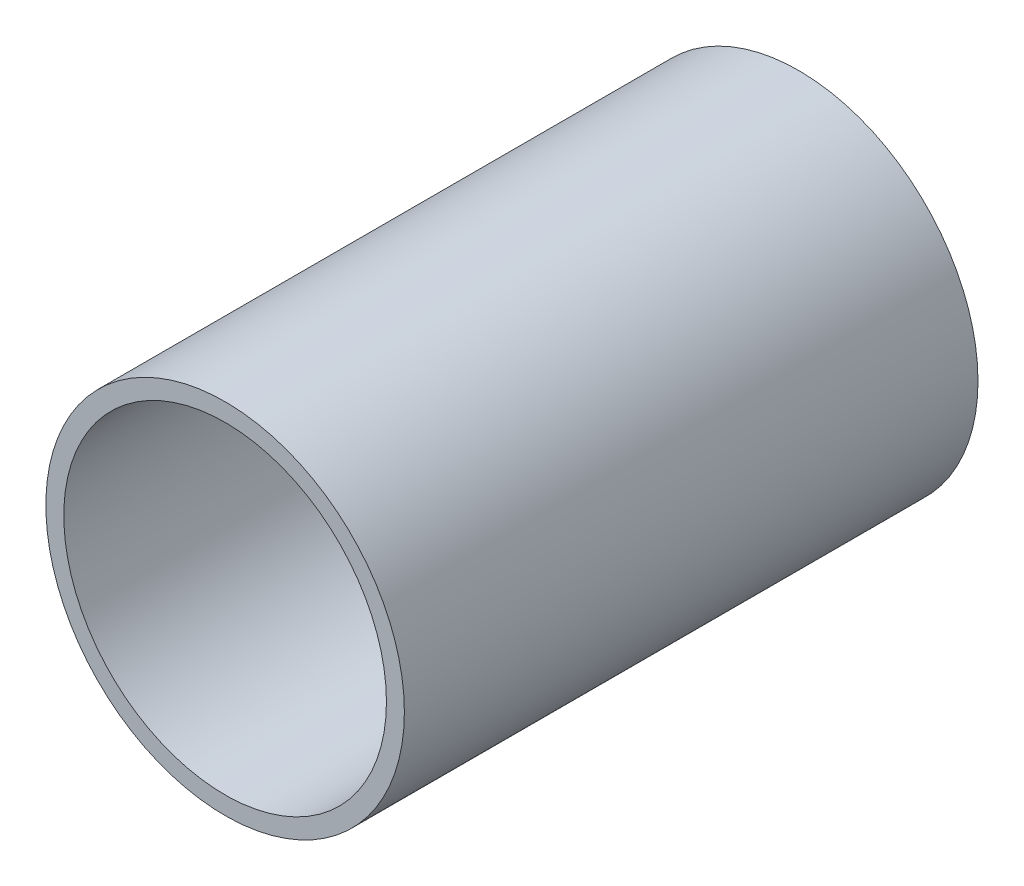
SolidWorks part; units mm, degrees
material "PVC Rigid"
ref_plane "Front" through (0, 0, 0) normal (0, 0, 1) x (1, 0, 0)
ref_plane "Top" through (0, 0, 0) normal (0, 1, 0) x (1, 0, 0)
ref_plane "Right" through (0, 0, 0) normal (1, 0, 0) x (0, 0, -1)
sketch "Sketch1" plane through (0, 0, 0) normal (0, 0, 1) x (1, 0, 0)
  circle A0 centre (0, 0) radius 45
  circle A1 centre (0, 0) radius 50
  dimension "D1" = 90
  dimension "D2" = 100
extrude "Boss-Extrude1" add sketch "Sketch1" along normal mid plane 160 contours A1
sketch "Sketch2" [suppressed] plane through (0, 0, 0) normal (0, 0, 1) x (1, 0, 0)
  circle A0 centre (0, 0) radius 45 construction
  circle A1 centre (0, 0) radius 45
extrude "Boss-Extrude2" [suppressed] add sketch "Sketch2" along normal mid plane 160
